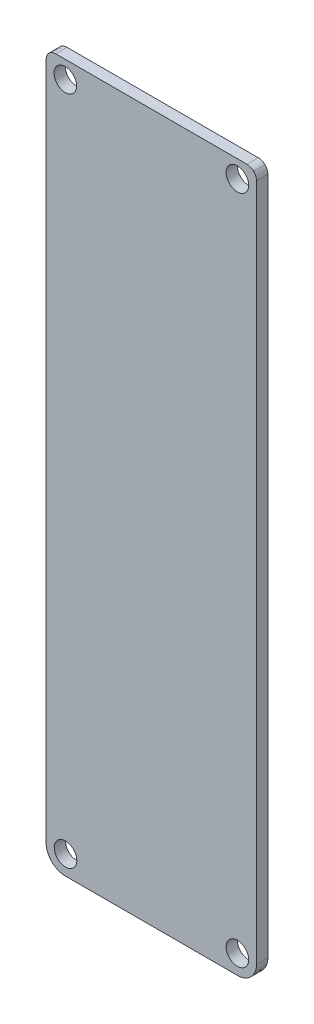
SolidWorks part; units mm, degrees
material "Verre"
ref_plane "Plan de face" through (0, 0, 0) normal (0, 0, 1) x (1, 0, 0)
ref_plane "Plan de dessus" through (0, 0, 0) normal (0, 1, 0) x (1, 0, 0)
ref_plane "Plan de droite" through (0, 0, 0) normal (1, 0, 0) x (0, 0, -1)
sketch "Model" plane through (0, 0, 0) normal (0, 0, 1) x (1, 0, 0)
  line L1773 (110.49, -33.6239) -> (110.49, -38.6239)
  line L1774 (83.82, -32.3539) -> (109.22, -32.3539)
  line L1775 (82.55, -38.6239) -> (82.55, -33.6239)
  line L1776 (82.55, -39.8939) -> (82.55, -123.7139)
  line L1777 (110.49, -39.8939) -> (110.49, -123.7139)
  line L1778 (82.55, -39.8939) -> (82.55, -38.6239)
  line L1779 (110.49, -39.8939) -> (110.49, -38.6239)
  line L1780 (85.09, -126.2539) -> (107.95, -126.2539)
  spline S12 degree 3 poles (110.49, -33.6239) (110.49, -33.2871) (110.3562, -32.9641) (110.118, -32.7259) knots 0 0 0 0 1 1 1 1
  spline S13 degree 3 poles (110.118, -32.7259) (109.8799, -32.4877) (109.5568, -32.3539) (109.22, -32.3539) knots 0 0 0 0 1 1 1 1
  spline S14 degree 3 poles (83.82, -32.3539) (83.4832, -32.3539) (83.1601, -32.4877) (82.922, -32.7259) knots 0 0 0 0 1 1 1 1
  spline S15 degree 3 poles (82.922, -32.7259) (82.6838, -32.9641) (82.55, -33.2871) (82.55, -33.6239) knots 0 0 0 0 1 1 1 1
  spline S16 degree 3 poles (82.55, -123.7139) (82.55, -124.3876) (82.8176, -125.0336) (83.2939, -125.51) knots 0 0 0 0 1 1 1 1
  spline S17 degree 3 poles (83.2939, -125.51) (83.7703, -125.9863) (84.4163, -126.2539) (85.09, -126.2539) knots 0 0 0 0 1 1 1 1
  spline S18 degree 3 poles (107.95, -126.2539) (108.6236, -126.2539) (109.2697, -125.9863) (109.7461, -125.51) knots 0 0 0 0 1 1 1 1
  spline S19 degree 3 poles (109.7461, -125.51) (110.2224, -125.0336) (110.49, -124.3876) (110.49, -123.7139) knots 0 0 0 0 1 1 1 1
  dimension "D1" = 5
  dimension "D2" = 5
extrude "Boss.-Extru.1" add sketch "Model" along normal blind 1.5
sketch "Esquisse2" plane through (0, 0, 1.5) normal (0, 0, 1) x (1, 0, 0)
  circle A0 centre (85.1248, -123.7139) radius 1.3048
  circle A1 centre (122.9136, -132.3177) radius 1.27
extrude "Enlèv. mat.-Extru.1" cut sketch "Esquisse2" against normal blind 10
sketch "Esquisse3" plane through (0, 0, 1.5) normal (0, 0, 1) x (1, 0, 0)
  circle A4 centre (107.9434, -123.7139) radius 1.3
extrude "Enlèv. mat.-Extru.2" cut sketch "Esquisse3" against normal blind 10
sketch "Esquisse4" plane through (0, 0, 0) normal (0, 0, -1) x (-1, 0, 0)
  line L0 (-107.9434, -36.1486) -> (-107.9434, -123.7139) construction
  line L1 (-107.9434, -36.1486) -> (-107.9434, -27.5158) construction
  line L2 (-96.52, -32.3539) -> (-96.52, -46.3277) construction
  line L3 (-109.22, -32.3539) -> (-83.82, -32.3539) construction
  circle A0 centre (-107.9434, -34.6757) radius 1.3
  circle A1 centre (-85.0966, -34.6757) radius 1.3
sketch "Esquisse5" plane through (0, 0, 0) normal (0, 0, -1) x (-1, 0, 0)
  line L0 (-107.9434, -36.1486) -> (-107.9434, -27.5158) construction
  line L1 (-96.52, -32.3539) -> (-96.52, -43.0789) construction
  line L2 (-109.22, -32.3539) -> (-83.82, -32.3539) construction
extrude "Enlèv. mat.-Extru.3" cut sketch "Esquisse4" against normal blind 10
sketch "Esquisse6" plane through (0, 0, 0) normal (0, 0, -1) x (-1, 0, 0)
  circle A0 centre (-107.9434, -34.6757) radius 1.5
  circle A1 centre (-85.0966, -34.6757) radius 1.5
  circle A2 centre (-85.1248, -123.7139) radius 1.5
  circle A3 centre (-107.9434, -123.7139) radius 1.5
extrude "Enlèv. mat.-Extru.4" cut sketch "Esquisse6" against normal blind 10
